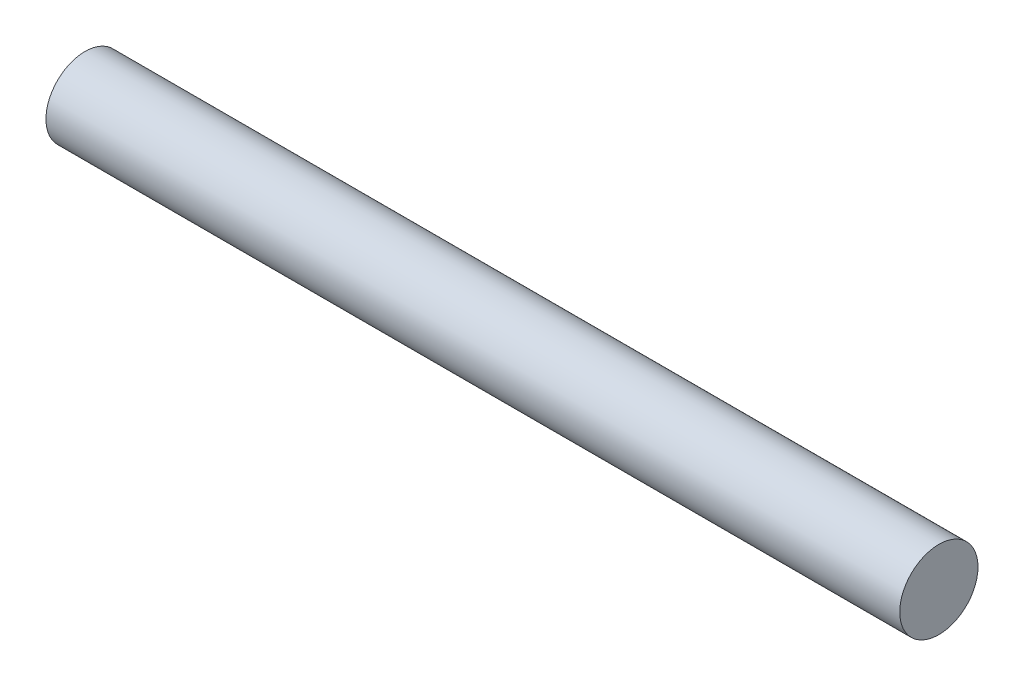
SolidWorks part; units mm, degrees
ref_plane "Front Plane" through (0, 0, 0) normal (0, 0, 1) x (1, 0, 0)
ref_plane "Top Plane" through (0, 0, 0) normal (0, 1, 0) x (1, 0, 0)
ref_plane "Right Plane" through (0, 0, 0) normal (1, 0, 0) x (0, 0, -1)
sketch "Sketch1" plane through (0, 0, 0) normal (1, 0, 0) x (0, 0, -1)
  circle A0 centre (0, 0) radius 1
  dimension "D1" = 2
extrude "Boss-Extrude1" add sketch "Sketch1" along normal mid plane 21.8187
